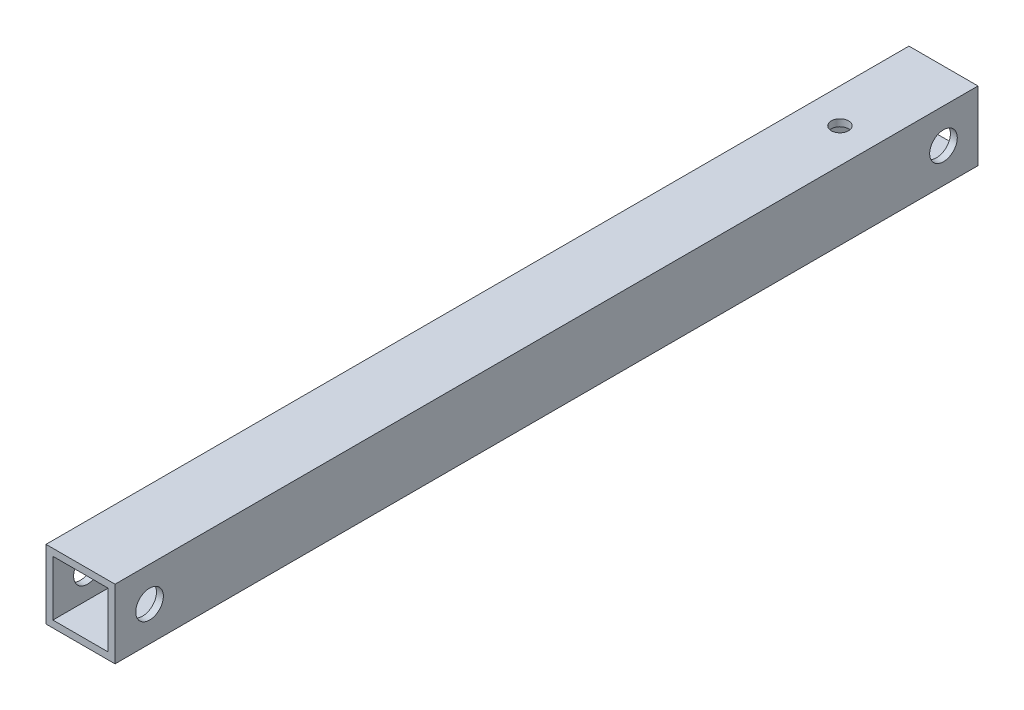
SolidWorks part; units mm, degrees
material "Stop 1060"
ref_plane "Płaszczyzna przednia" through (0, 0, 0) normal (0, 0, 1) x (1, 0, 0)
ref_plane "Płaszczyzna górna" through (0, 0, 0) normal (0, 1, 0) x (1, 0, 0)
ref_plane "Płaszczyzna prawa" through (0, 0, 0) normal (1, 0, 0) x (0, 0, -1)
sketch "Szkic1" plane through (0, 0, 0) normal (0, 0, 1) x (1, 0, 0)
  line L0 (-8, 8) -> (8, 8)
  line L1 (-10, -10) -> (10, -10)
  line L2 (-10, -10) -> (-10, 10)
  line L3 (-10, 10) -> (10, 10)
  line L4 (10, -10) -> (10, 10)
  line L5 (-10, -10) -> (10, 10) construction
  line L6 (-10, 10) -> (10, -10) construction
  line L7 (8, -8) -> (8, 8)
  line L8 (-8, -8) -> (8, -8)
  line L9 (-8, -8) -> (-8, 8)
  point P0 (0, 0)
  dimension "D1" = 20
  dimension "D2" = 20
  dimension "D3" = 2
extrude "Dodanie-wyciągnięcie1" add sketch "Szkic1" along normal blind 250
sketch "Szkic2" plane through (10, 0, 0) normal (1, 0, 0) x (0, 0, -1)
  line L0 (0, -10) -> (0, 10) construction
  line L3 (-250, -10) -> (-250, 10) construction
  circle A0 centre (-10, 0) radius 4
  circle A1 centre (-240, 0) radius 4
  dimension "D1" = 8
  dimension "D3" = 8
  dimension "D2" = 10
  dimension "D4" = 10
extrude "Wytnij-wyciągnięcie1" cut sketch "Szkic2" against normal through all
sketch "Szkic3" plane through (0, 10, 0) normal (0, 1, 0) x (1, 0, 0)
  line L0 (10, -250) -> (10, 0) construction
  line L2 (10, 0) -> (-10, 0) construction
  circle A0 centre (0, -30) radius 2.5
  dimension "D1" = 5
  dimension "D2" = 10
  dimension "D3" = 30
extrude "Wytnij-wyciągnięcie2" cut sketch "Szkic3" against normal through all
